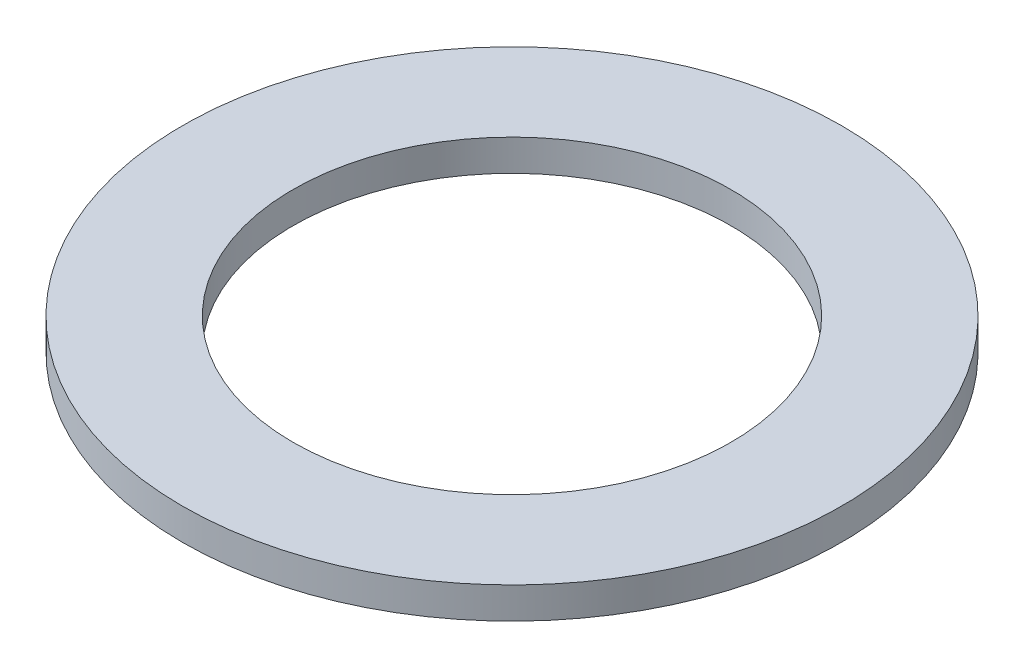
SolidWorks part; units mm, degrees
ref_plane "Front Plane" through (0, 0, 0) normal (0, 0, 1) x (1, 0, 0)
ref_plane "Top Plane" through (0, 0, 0) normal (0, 1, 0) x (1, 0, 0)
ref_plane "Right Plane" through (0, 0, 0) normal (1, 0, 0) x (0, 0, -1)
sketch "Sketch1" plane through (0, 0, 0) normal (0, 1, 0) x (1, 0, 0)
  circle A0 centre (0, 0) radius 6.977
  circle A1 centre (0, 0) radius 10.5
  dimension "D1" = 13.954
  dimension "D2" = 21
extrude "Boss-Extrude1" add sketch "Sketch1" along normal blind 1
